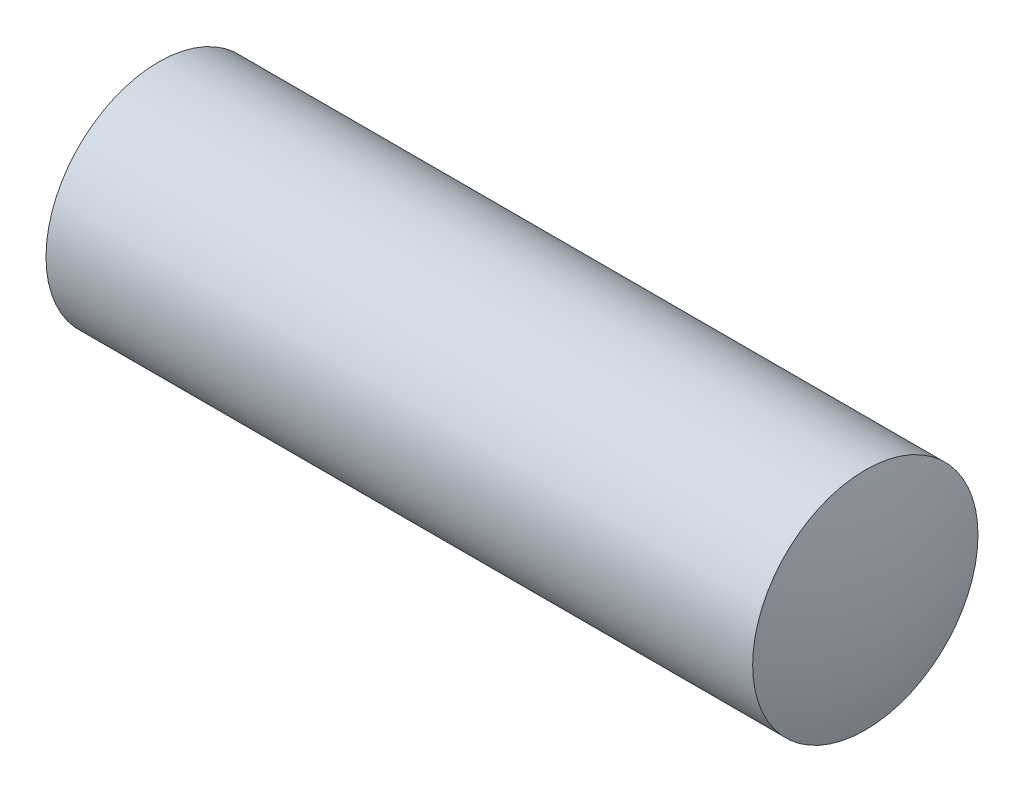
SolidWorks part; units mm, degrees
material "Простая углеродистая сталь"
ref_plane "Спереди" through (0, 0, 0) normal (0, 0, 1) x (1, 0, 0)
ref_plane "Сверху" through (0, 0, 0) normal (0, 1, 0) x (1, 0, 0)
ref_plane "Справа" through (0, 0, 0) normal (1, 0, 0) x (0, 0, -1)
sketch "Эскиз1" plane through (0, 0, 0) normal (0, 0, 1) x (1, 0, 0)
  line L1 (18.804, 6) -> (-18.8288, 6)
  line L2 (-19.9597, 0) -> (19.4854, 0) construction
  line L3 (19.75, 0) -> (-19.75, 0)
  arc A0 (-18.8288, 6) -> (-19.75, 0) centre (0.25, 0) ccw
  arc A1 (18.804, 6) -> (19.75, 0) centre (0.25, 0) cw
  dimension "R" = 20
  dimension "D" = 12
  dimension "L" = 39.5
revolve "Повернуть1" add sketch "Эскиз1" angle 360 about L2
